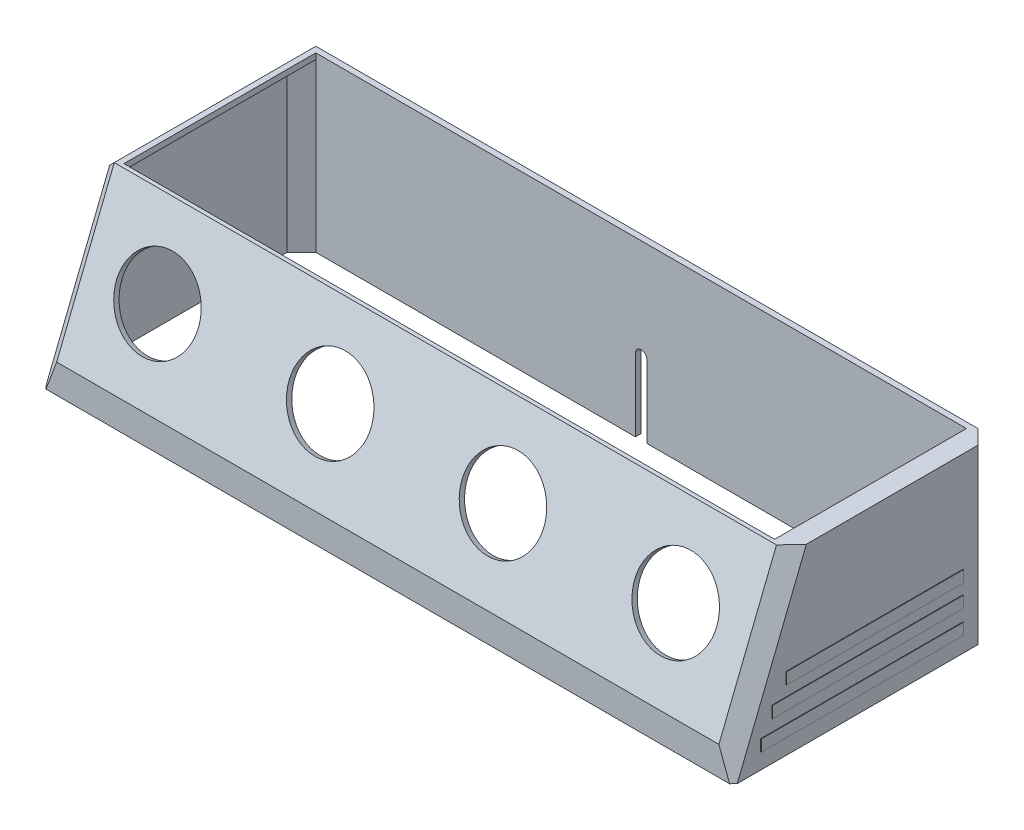
SolidWorks part; units mm, degrees
ref_plane "Alzado" through (0, 0, 0) normal (0, 0, 1) x (1, 0, 0)
ref_plane "Planta" through (0, 0, 0) normal (0, 1, 0) x (1, 0, 0)
ref_plane "Vista lateral" through (0, 0, 0) normal (1, 0, 0) x (0, 0, -1)
sketch "Croquis1" plane through (0, 0, 0) normal (0, 1, 0) x (1, 0, 0)
  line L1 (-120, -45) -> (120, -45)
  line L2 (-120, -45) -> (-120, 45)
  line L3 (-120, 45) -> (120, 45)
  line L4 (120, -45) -> (120, 45)
  line L5 (-120, -45) -> (120, 45) construction
  line L6 (-120, 45) -> (120, -45) construction
  point P0 (0, 0)
  dimension "D1" = 240
  dimension "D2" = 90
extrude "Saliente-Extruir1" add sketch "Croquis1" along normal blind 60
sketch "Croquis2" plane through (120, 0, 0) normal (1, 0, 0) x (0, 0, -1)
  line L0 (-45, 10) -> (-25, 60)
  line L1 (-45, 60) -> (-45, 0) construction
  line L2 (-45, 60) -> (45, 60) construction
  line L3 (-25, 60) -> (-45, 60)
  line L4 (-45, 60) -> (-45, 10)
  point P6 (-25.9641, 60)
  dimension "D1" = 50
  dimension "D2" = 20
extrude "Cortar-Extruir1" cut sketch "Croquis2" against normal up to vertex (240 mm away)
shell "Vaciado1" thickness 2
sketch "Croquis3" plane through (0, 16.8966, 42.2414) normal (0, 0.3714, 0.9285) x (1, 0, 0)
  line L0 (-120, 19.498) -> (120, 19.498) construction
  line L1 (-120, -7.4278) -> (-120, 46.4238) construction
  line L2 (120, -7.4278) -> (120, 46.4238) construction
  circle A0 centre (-90, 19.498) radius 14.25
  circle A1 centre (-30, 19.498) radius 14.25
  circle A2 centre (30, 19.498) radius 14.25
  circle A3 centre (90, 19.498) radius 14.25
  dimension "D1" = 28.5
  dimension "D2" = 60
  dimension "D3" = 60
  dimension "D4" = 60
  dimension "D5" = 30
extrude "Cortar-Extruir2" cut sketch "Croquis3" against normal up to vertex (2 mm away)
sketch "Croquis4" plane through (120, 0, 0) normal (1, 0, 0) x (0, 0, -1)
  line L1 (-35.4701, 5.4569) -> (34.7311, 5.4569)
  line L2 (-35.4701, 5.4569) -> (-35.4701, 9.4569)
  line L3 (-35.4701, 9.4569) -> (34.7311, 9.4569)
  line L4 (34.7311, 5.4569) -> (34.7311, 9.4569)
  line L5 (-31.6275, 13.5951) -> (34.7311, 13.5951)
  line L6 (-31.6275, 13.5951) -> (-31.6275, 17.5951)
  line L7 (-31.6275, 17.5951) -> (34.7311, 17.5951)
  line L8 (34.7311, 13.5951) -> (34.7311, 17.5951)
  line L9 (-26.7504, 21.2803) -> (34.7311, 21.2803)
  line L10 (-26.7504, 21.2803) -> (-26.7504, 25.2803)
  line L11 (-26.7504, 25.2803) -> (34.7311, 25.2803)
  line L12 (34.7311, 21.2803) -> (34.7311, 25.2803)
  dimension "D1" = 4
  dimension "D2" = 4
  dimension "D3" = 4
fillet "Chaflán1" radius 5 11 edges at (-120, 35, 35) (-118, 33.8074, 33.323) (118, 33.8074, 33.323) (120, 35, 35) (-120, 60, -10) (-120, 30, -45) (-118, 29, -43) (-118, 58, -9.677) (118, 58, -9.677) (120, 30, -45) (118, 29, -43) profile chamfer
sketch "Croquis6" plane through (0, 58, 0) normal (0, -1, 0) x (1, 0, 0)
  line L4 (113, 23.6459) -> (-113, 23.6459)
  line L5 (-113, 23.6459) -> (-113, -43)
  line L6 (-113, -43) -> (113, -43)
  line L7 (113, -43) -> (113, 23.6459)
  line L8 (113, 23.6459) -> (-113, 23.6459)
  line L9 (-113, 23.6459) -> (-113, -43)
  line L10 (-113, -43) -> (113, -43)
  line L11 (113, -43) -> (113, 23.6459)
  dimension "D1" = 0
extrude "Cortar-Extruir6" cut sketch "Croquis6" against normal up to vertex (2 mm away)
extrude "Saliente-Extruir4" add sketch "Croquis4" along normal blind 0.2
sketch "Croquis7" plane through (-120, 0, 0) normal (-1, 0, 0) x (0, 0, 1)
  line L4 (-34.7311, 21.2803) -> (26.7504, 21.2803)
  line L5 (-34.7311, 25.2803) -> (-34.7311, 21.2803)
  line L6 (26.7504, 25.2803) -> (-34.7311, 25.2803)
  line L7 (26.7504, 21.2803) -> (26.7504, 25.2803)
  line L8 (-34.7311, 21.2803) -> (26.7504, 21.2803)
  line L9 (-34.7311, 25.2803) -> (-34.7311, 21.2803)
  line L10 (26.7504, 25.2803) -> (-34.7311, 25.2803)
  line L11 (26.7504, 21.2803) -> (26.7504, 25.2803)
  line L12 (-34.7311, 13.5951) -> (31.6275, 13.5951)
  line L13 (-34.7311, 17.5951) -> (-34.7311, 13.5951)
  line L14 (31.6275, 17.5951) -> (-34.7311, 17.5951)
  line L15 (31.6275, 13.5951) -> (31.6275, 17.5951)
  line L16 (-34.7311, 13.5951) -> (31.6275, 13.5951)
  line L17 (-34.7311, 17.5951) -> (-34.7311, 13.5951)
  line L18 (31.6275, 17.5951) -> (-34.7311, 17.5951)
  line L19 (31.6275, 13.5951) -> (31.6275, 17.5951)
  line L20 (-34.7311, 5.4569) -> (35.4701, 5.4569)
  line L21 (-34.7311, 9.4569) -> (-34.7311, 5.4569)
  line L22 (35.4701, 9.4569) -> (-34.7311, 9.4569)
  line L23 (35.4701, 5.4569) -> (35.4701, 9.4569)
  line L24 (-34.7311, 5.4569) -> (35.4701, 5.4569)
  line L25 (-34.7311, 9.4569) -> (-34.7311, 5.4569)
  line L26 (35.4701, 9.4569) -> (-34.7311, 9.4569)
  line L27 (35.4701, 5.4569) -> (35.4701, 9.4569)
  dimension "D1" = 0
  dimension "D2" = 0
  dimension "D3" = 0
extrude "Cortar-Extruir7" cut sketch "Croquis7" against normal blind 0.2
sketch "Croquis9" plane through (0, 0, -45) normal (0, 0, -1) x (-1, 0, 0)
  line L0 (-2, 0) -> (2, 0)
  line L2 (-2, 0) -> (-2, 25.2276)
  line L4 (2, 0) -> (2, 25.2276)
  line L6 (-1.975, 24.9125) -> (0, 0) construction
  arc A0 (2, 25.2276) -> (-2, 25.2276) centre (0, 25.2276) ccw
  point P0 (0, 0)
  dimension "D1" = 4
extrude "Cortar-Extruir8" cut sketch "Croquis9" against normal blind 10
